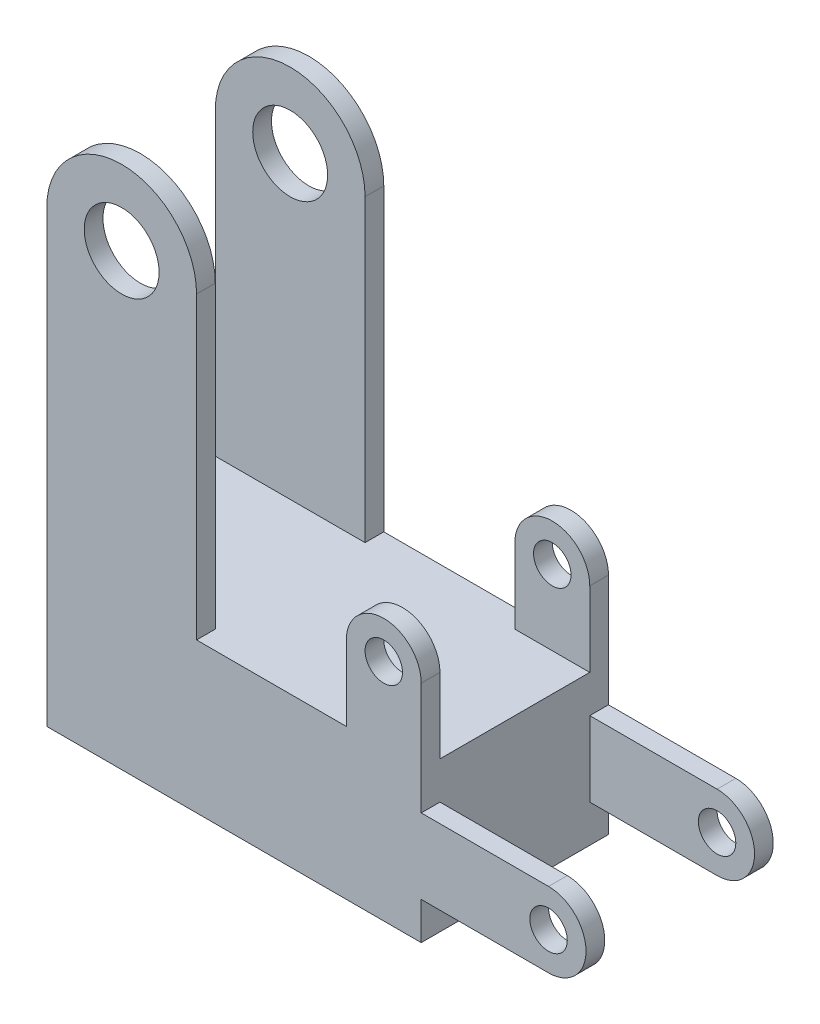
SolidWorks part; units mm, degrees
ref_plane "Front Plane" through (0, 0, 0) normal (0, 0, 1) x (1, 0, 0)
ref_plane "Top Plane" through (0, 0, 0) normal (0, 1, 0) x (1, 0, 0)
ref_plane "Right Plane" through (0, 0, 0) normal (1, 0, 0) x (0, 0, -1)
sketch "Sketch1" plane through (0, 0, 0) normal (0, 0, 1) x (1, 0, 0)
  line L1 (-49.0617, -20.2443) -> (-49.0617, 39.7557)
  line L2 (-29.0617, 39.7557) -> (-29.0617, -0.2443)
  line L3 (-29.0617, -0.2443) -> (-9.0617, -0.2443)
  line L4 (-9.0617, -0.2443) -> (-9.0617, 9.7557)
  line L7 (0.9383, -5.2443) -> (17.9383, -5.2443)
  line L8 (17.9383, -15.2443) -> (0.9383, -15.2443)
  line L9 (0.9383, -15.2443) -> (0.9383, -20.2443)
  line L11 (-49.0617, -20.2443) -> (0.9383, -20.2443)
  line L12 (0.9383, 9.7557) -> (0.9383, -5.2443)
  arc A0 (-49.0617, 39.7557) -> (-29.0617, 39.7557) centre (-39.0617, 39.7557) cw
  arc A1 (-9.0617, 9.7557) -> (0.9383, 9.7557) centre (-4.0617, 9.7557) cw
  arc A2 (17.9383, -5.2443) -> (17.9383, -15.2443) centre (17.9383, -10.2443) cw
  dimension "D5" = 10
  dimension "D7" = 5
  dimension "D8" = 5
  dimension "D1" = 50
  dimension "D2" = 60
  dimension "D3" = 40
  dimension "D4" = 10
  dimension "D6" = 17
  dimension "D9" = 17
  dimension "D11" = 5
extrude "Boss-Extrude1" add sketch "Sketch1" along normal blind 25
sketch "Sketch3" plane through (-29.0617, 0, 0) normal (1, 0, 0) x (0, 0, -1)
  line L0 (-25, -0.2443) -> (0, -0.2443) construction
  line L1 (-22.5, -0.2443) -> (-2.5, -0.2443)
  line L2 (-22.5, -0.2443) -> (-22.5, 56.5515)
  line L3 (-22.5, 56.5515) -> (-2.5, 56.5515)
  line L4 (-2.5, -0.2443) -> (-2.5, 56.5515)
  line L5 (-25, 9.7557) -> (0, 9.7557) construction
  point P6 (-12.5, -0.2443)
  point P9 (-12.5, 9.7557)
  dimension "D1" = 20
extrude "Cut-Extrude2" cut sketch "Sketch3" against normal through all and the other way through all
sketch "Sketch4" plane through (0, 0, 25) normal (0, 0, 1) x (1, 0, 0)
  circle A0 centre (-39.0617, 39.7557) radius 5
  dimension "D1" = 10
extrude "Cut-Extrude3" cut sketch "Sketch4" against normal through all
sketch "Sketch5" plane through (0, 0, 25) normal (0, 0, 1) x (1, 0, 0)
  circle A0 centre (-4.0617, 9.7557) radius 2.5
  dimension "D1" = 5
extrude "Cut-Extrude4" cut sketch "Sketch5" against normal through all
sketch "Sketch7" plane through (0, -5.2443, 0) normal (0, 1, 0) x (1, 0, 0)
  line L1 (0.9383, -22.5) -> (26.589, -22.5)
  line L2 (0.9383, -22.5) -> (0.9383, -2.5)
  line L3 (0.9383, -2.5) -> (26.589, -2.5)
  line L4 (26.589, -22.5) -> (26.589, -2.5)
  dimension "D1" = 20
extrude "Cut-Extrude5" cut sketch "Sketch7" against normal up to next
sketch "Sketch8" plane through (0, 0, 25) normal (0, 0, 1) x (1, 0, 0)
  circle A0 centre (17.9383, -10.2443) radius 2.5
  dimension "D1" = 5
extrude "Cut-Extrude6" cut sketch "Sketch8" against normal through all
